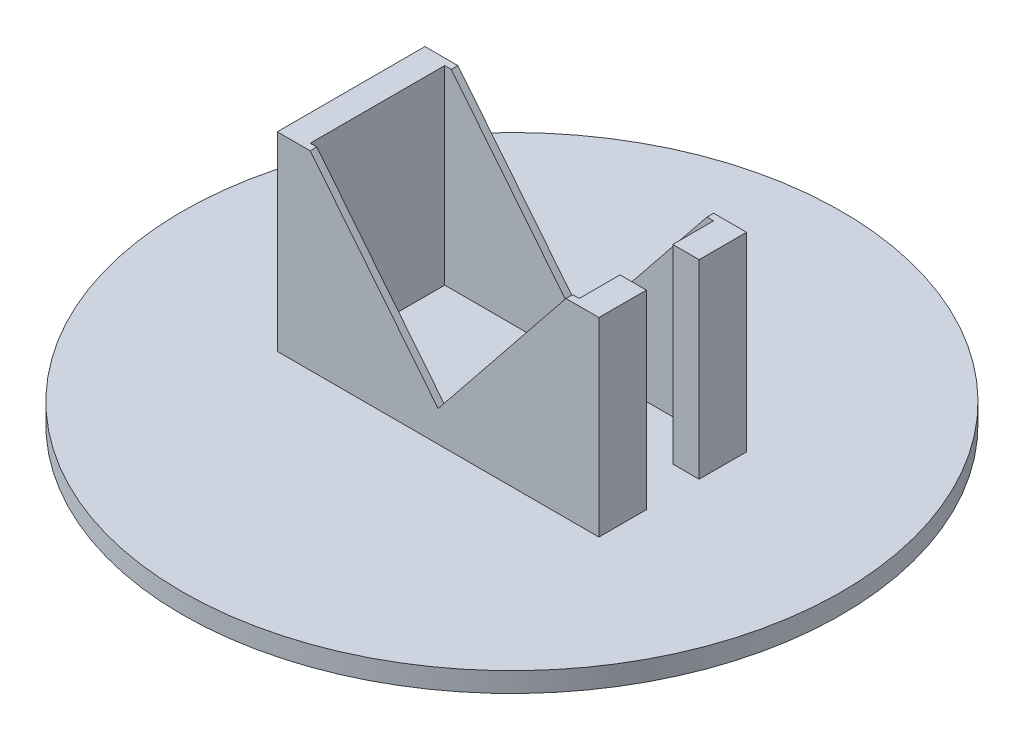
SolidWorks part; units mm, degrees
ref_plane "Ebene vorne" through (0, 0, 0) normal (0, 0, 1) x (1, 0, 0)
ref_plane "Ebene oben" through (0, 0, 0) normal (0, 1, 0) x (1, 0, 0)
ref_plane "Ebene rechts" through (0, 0, 0) normal (1, 0, 0) x (0, 0, -1)
sketch "Skizze1" plane through (0, 0, 0) normal (0, 1, 0) x (1, 0, 0)
  circle A0 centre (0, 0) radius 50
  dimension "D1" = 100
extrude "Aufsatz-Linear austragen1" add sketch "Skizze1" along normal blind 3
sketch "Skizze2" plane through (0, 3, 0) normal (0, 1, 0) x (1, 0, 0)
  line L0 (20.4, 4) -> (24.4, 4)
  line L1 (-20.4, -10.2) -> (20.4, -10.2)
  line L2 (-20.4, -10.2) -> (-20.4, 10.2)
  line L3 (-20.4, 10.2) -> (20.4, 10.2)
  line L4 (20.4, -10.2) -> (20.4, -4)
  line L5 (-20.4, -10.2) -> (20.4, 10.2) construction
  line L6 (-20.4, 10.2) -> (20.4, -10.2) construction
  line L7 (-24.4, -11.2) -> (24.4, -11.2)
  line L8 (-24.4, -11.2) -> (-24.4, 11.2)
  line L9 (-24.4, 11.2) -> (24.4, 11.2)
  line L10 (24.4, -11.2) -> (24.4, -4)
  line L11 (-24.4, -11.2) -> (24.4, 11.2) construction
  line L12 (-24.4, 11.2) -> (24.4, -11.2) construction
  line L13 (20.4, -4) -> (24.4, -4)
  line L14 (-55, 0) -> (55, 0) construction
  line L15 (20.4, 4) -> (20.4, 10.2)
  line L16 (24.4, 4) -> (24.4, 11.2)
  point P0 (0, 0)
  point P6 (0, 0)
  dimension "D1" = 40.8
  dimension "D2" = 20.4
  dimension "D3" = 48.8
  dimension "D4" = 22.4
  dimension "D5" = 4
  dimension "D6" = 4
extrude "Aufsatz-Linear austragen2" add sketch "Skizze2" along normal blind 28.85
sketch "Skizze3" plane through (0, 0, 11.2) normal (0, 0, 1) x (1, 0, 0)
  line L0 (-19.4, 31.85) -> (0, 7.6812)
  line L1 (-24.4, 31.85) -> (24.4, 31.85) construction
  line L2 (0, -55) -> (0, 55) construction
  line L3 (0, 7.6812) -> (19.4, 31.85)
  line L4 (19.4, 31.85) -> (-19.4, 31.85)
  line L5 (-24.4, 31.85) -> (-24.4, 3) construction
  line L6 (24.4, 31.85) -> (24.4, 3) construction
  dimension "D1" = 5
  dimension "D2" = 5
extrude "Schnitt-Linear austragen1" cut sketch "Skizze3" against normal blind 28.85
